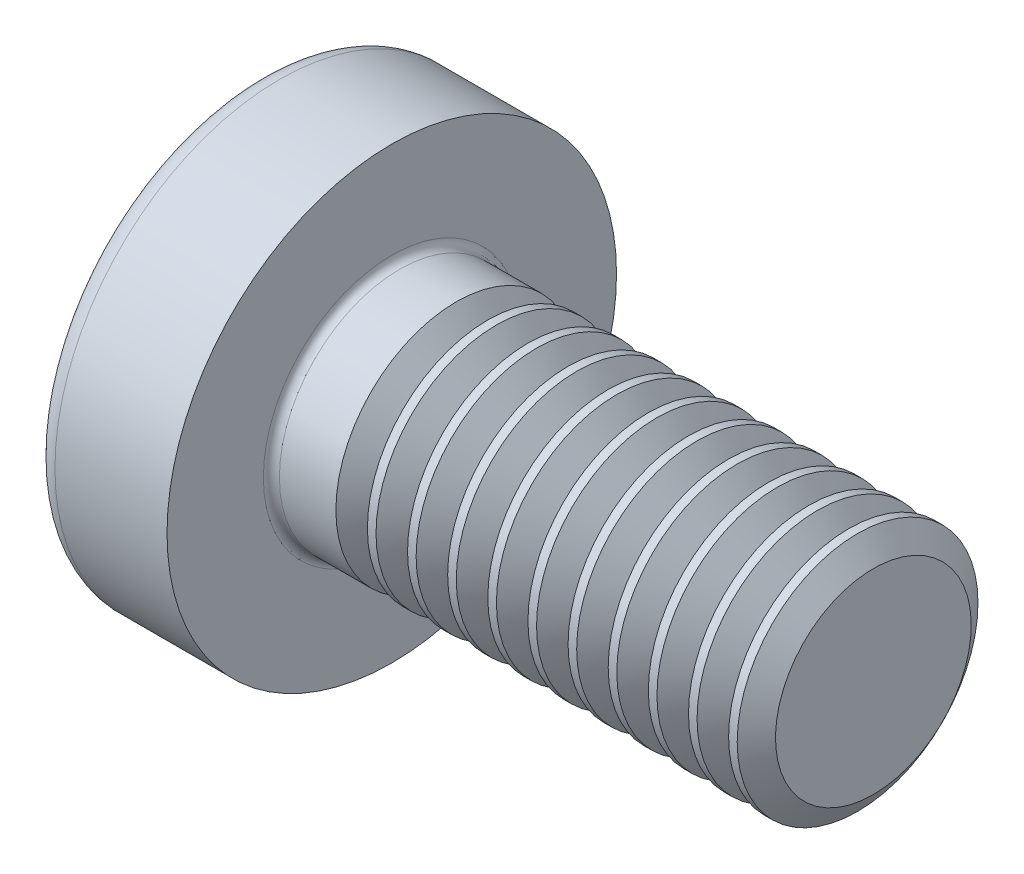
SolidWorks part; units mm, degrees
ref_plane "Plane1" through (0, 0, 0) normal (0, 0, 1) x (1, 0, 0)
ref_plane "Plane2" through (0, 0, 0) normal (0, 1, 0) x (1, 0, 0)
ref_plane "Plane3" through (0, 0, 0) normal (1, 0, 0) x (0, 0, -1)
sketch "BodySke" plane through (0, 0, 0) normal (0, 0, 1) x (1, 0, 0)
  line L0 (2.4, 1.5) -> (2.4, 2.8)
  line L1 (2.65, 6.35) -> (2.65, -3.175) construction
  line L2 (-25.4, 0) -> (127, 0) construction
  line L3 (8.4, 0) -> (0, 0)
  line L4 (2.4, 1.5) -> (8.4, 1.5)
  line L5 (8.4, 1.5) -> (8.4, 0)
  line L6 (1.0035, 2.8) -> (2.4, 2.8)
  line L8 (2.4, 6.35) -> (2.4, -3.175) construction
  arc A0 (0.7754, 2.6744) -> (0, 0) centre (5, 0) ccw
  arc A2 (0.7754, 2.6744) -> (1.0035, 2.8) centre (1.0035, 2.53) cw
  dimension "Head_crown_rad" = 5
  dimension "Head_fillet_rad" = 0.27
  dimension "Length" = 6
  dimension "Head_ht" = 2.4
  dimension "Head_dia" = 5.6
  dimension "Advance" = 0.5
  dimension "Thread_nom" = 6
  dimension "Diameter" = 3
revolve "Base-Revolve" add sketch "BodySke"
cosmetic thread "ThreadCosmetic" [suppressed]
fillet "Fillet1" radius 0.1 1 edges at (2.4, 0, 1.5)
sketch "Sketch3" plane through (0, 0, 0) normal (1, 0, 0) x (0, 0, -1)
  line L0 (0.37, -1.4) -> (-0.37, -1.4)
  line L1 (0.37, -1.4) -> (0.37, 1.4)
  line L2 (-0.37, 1.4) -> (0.37, 1.4)
  line L3 (-0.37, 1.4) -> (-0.37, -1.4)
  dimension "Cross_dia" = 2.8
  dimension "D1" = 1.4
  dimension "Cross_width" = 0.74
  dimension "D2" = 0.37
ref_plane "Plane4" through (1.75, 0, 0) normal (1, 0, 0) x (0, 0, -1)
sketch "Sketch4" plane through (1.75, 0, 0) normal (1, 0, 0) x (0, 0, -1)
  line L0 (0.37, -0.5275) -> (-0.37, -0.5275)
  line L1 (0.37, -0.5275) -> (0.37, 0.5275)
  line L2 (-0.37, 0.5275) -> (0.37, 0.5275)
  line L3 (-0.37, 0.5275) -> (-0.37, -0.5275)
  dimension "D1" = 0.74
  dimension "D2" = 1.055
  dimension "D3" = 0.37
  dimension "D4" = 0.5275
loft "Recess" cut profiles "Sketch3", "Sketch4"
pattern_circular "RecPat" count 2 every 90 about axis through (0, 0, 0) along (1, 0, 0) of "Recess"
sketch "RecCorSke" plane through (0, 0, 0) normal (0, 0, 1) x (1, 0, 0)
  line L0 (-3.175, 0) -> (15.875, 0) construction
  line L1 (-25.4, 0) -> (127, 0) construction
  line L2 (0, 0) -> (0, 0.6784)
  line L3 (0, 0.6784) -> (1.75, 0.556)
  line L4 (1.75, 0.556) -> (1.9307, 0)
  line L5 (1.9307, 0) -> (0, 0)
  dimension "Diameter" = 1.112
  dimension "Depth" = 1.75
  dimension "Draft_angle" = 4
  dimension "Bottom_angle" = 18
revolve "RecessCore" cut sketch "RecCorSke" angle 360 about L0
sketch "ThdSchSke" plane through (0, 0, 0) normal (0, 0, 1) x (1, 0, 0)
  line L0 (3.4, -1.2195) -> (3.2036, -1.5)
  line L1 (3.4, -1.2195) -> (3.5964, -1.5)
  line L2 (3.5964, -1.5) -> (3.5964, -1.875)
  line L3 (-3.175, 0) -> (5.1513, 0) construction
  line L5 (3.5964, -1.875) -> (3.2036, -1.875)
  line L6 (3.2036, -1.875) -> (3.2036, -1.5)
  dimension "Diameter" = 3
  dimension "SideAngle" = 55
  dimension "VeeAngle" = 70
  dimension "Thread_minor" = 2.439
  dimension "Overcut" = 3.75
  dimension "Start" = 3.4
revolve "ThreadSchematic" cut sketch "ThdSchSke" angle 360 about L3
pattern_linear "ThdSchPat" count 11 spacing 0.5 along (1, 0, 0) of "ThreadSchematic"
equation "\"D1@Sketch3\" = \"Cross_dia@Sketch3\" / 2"
equation "\"D2@Sketch3\" = \"Cross_width@Sketch3\" / 2"
equation "\"Depth@RecCorSke\" = \"Cross_depth@Plane4\""
equation "\"D1@Sketch4\" = \"Cross_width@Sketch3\""
equation "\"D2@Sketch4\" = \"Cross_dia@Sketch3\" - 2.0 * \"Cross_depth@Plane4\" * tan(26.5  * 0.017453292)"
equation "\"D3@Sketch4\" = \"D1@Sketch4\" / 2"
equation "\"D4@Sketch4\" = \"D2@Sketch4\" / 2"
equation "\"Thread_length@ThreadCosmetic\" = ((sgn( (\"Length@BodySke\" - \"Advance@BodySke\" * 2.0 ) - \"Thread_nom@BodySke\" )-1)*( (\"Length@BodySke\" - \"Advance@BodySke\" * 2.0 ) - \"Thread_nom@BodySke\" ))/-2+ \"Thread_nom@BodySke\""
equation "\"Thread_minor@ThdSchSke\" = \"Thread_minor@ThreadCosmetic\""
equation "\"Diameter@ThdSchSke\" = \"Diameter@BodySke\""
equation "\"Overcut@ThdSchSke\" = \"Diameter@BodySke\" * 1.25"
equation "\"Start@ThdSchSke\" = \"Head_ht@BodySke\" + \"Length@BodySke\" - \"Thread_length@ThreadCosmetic\"  '---Non-countersunk---"
equation "\"Num_threads@ThdSchPat\" = int( \"Thread_length@ThreadCosmetic\" / \"Advance@BodySke\" + 0.999 )  + 1"
equation "\"Advance@ThdSchPat\" = \"Thread_length@ThreadCosmetic\" /  (\"Num_threads@ThdSchPat\" - 1) 'relax it"
